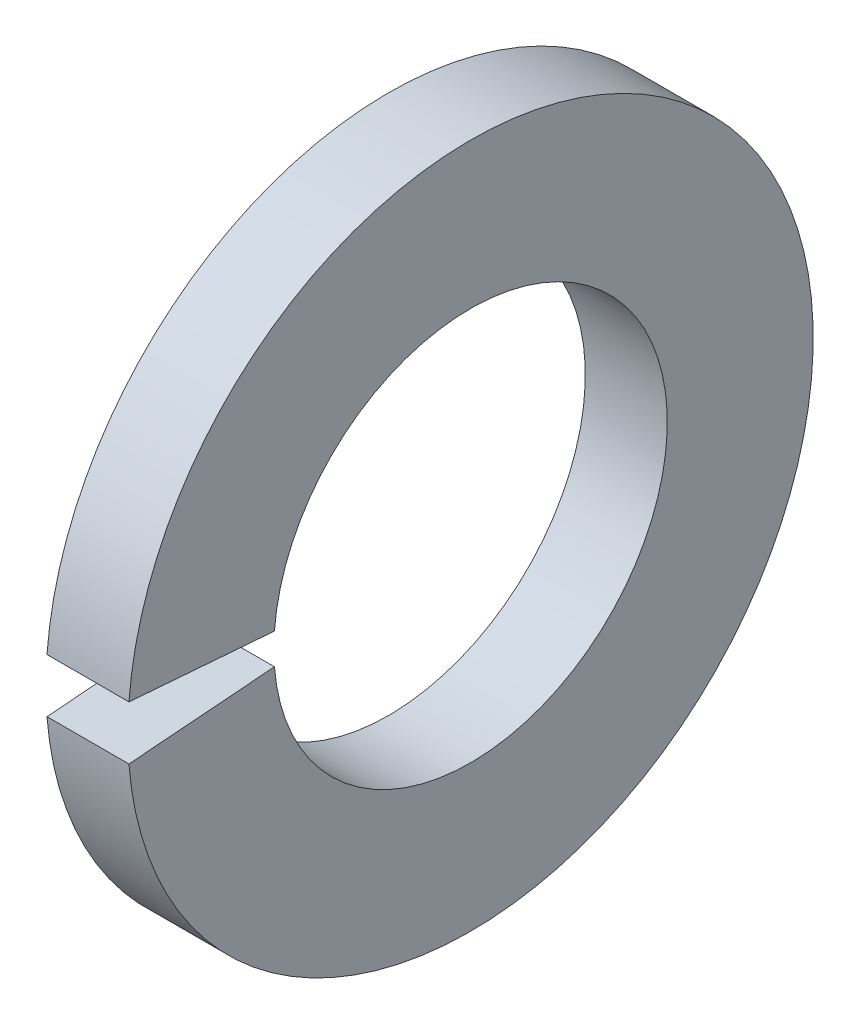
SolidWorks part; units mm, degrees
other "Defeature"
material "Alloy Steel"
ref_plane "Plane1" through (0, 0, 0) normal (0, 0, 1) x (1, 0, 0)
ref_plane "Plane2" through (0, 0, 0) normal (0, 1, 0) x (1, 0, 0)
ref_plane "Plane3" through (0, 0, 0) normal (1, 0, 0) x (0, 0, -1)
sketch "Sketch1" plane through (0, 0, 0) normal (0, 0, 1) x (1, 0, 0)
  line L0 (-34.925, 0) -> (9.525, 0) construction
  line L1 (0, 1.524) -> (0, 2.6543)
  line L2 (0, 2.6543) -> (-0.635, 2.6543)
  line L3 (-0.635, 2.6543) -> (-0.635, 1.524)
  line L4 (-0.635, 1.524) -> (0, 1.524)
  dimension "Thickness" = 0.635
  dimension "Inside_dia" = 3.048
  dimension "Outside_dia" = 5.3086
revolve "Base-Revolve" add sketch "Sketch1" angle 360 about L0
sketch "Sketch2" plane through (0, 0, 0) normal (-1, 0, 0) x (0, -1, 0)
  line L0 (0, 0) -> (0.2124, 2.699)
  line L1 (0, -3.175) -> (0, 12.7) construction
  line L2 (0, 0) -> (-0.2124, 2.699)
  arc A0 (0.2124, 2.699) -> (-0.2124, 2.699) centre (0, 0) ccw
  dimension "Gap_ang" = 9
  dimension "D1" = 2.7074
extrude "Gap" cut sketch "Sketch2" along normal through all
equation "\"D1@Sketch2\" = \"Outside_dia@Sketch1\" * 0.51"
